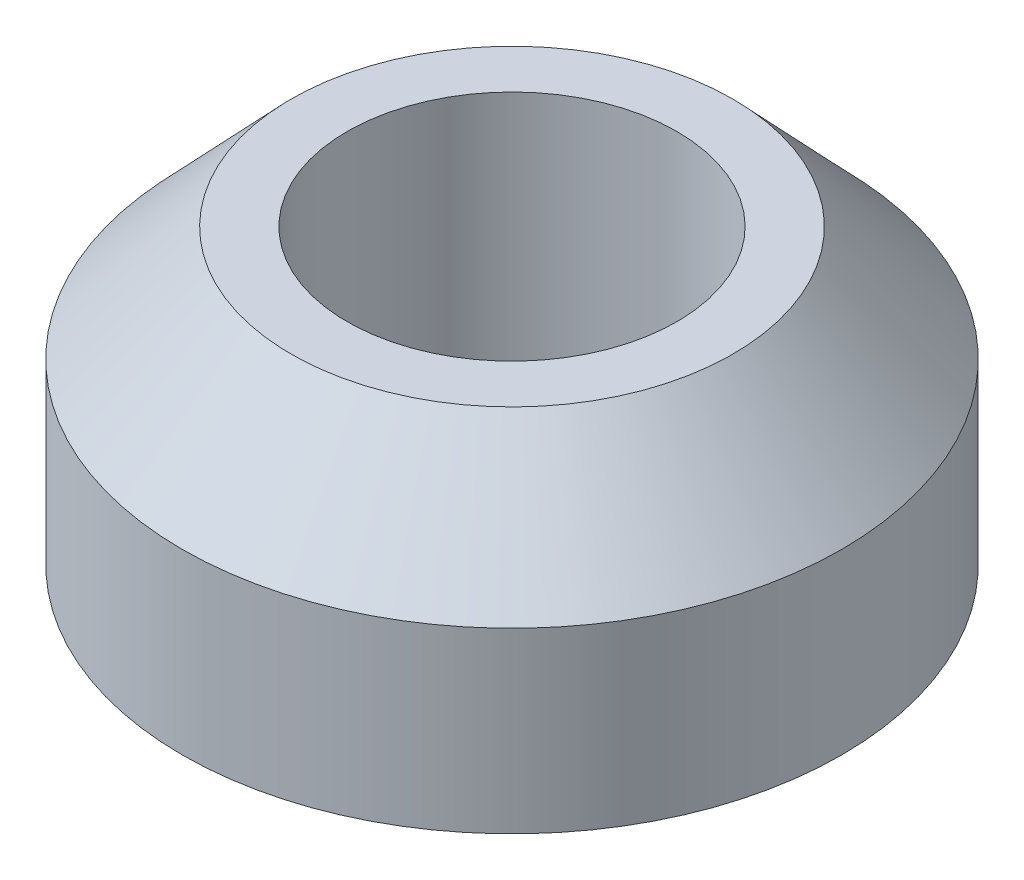
SolidWorks part; units mm, degrees
material "Alloy Steel"
ref_plane "Front Plane" through (0, 0, 0) normal (0, 0, 1) x (1, 0, 0)
ref_plane "Top Plane" through (0, 0, 0) normal (0, 1, 0) x (1, 0, 0)
ref_plane "Right Plane" through (0, 0, 0) normal (1, 0, 0) x (0, 0, -1)
sketch "Sketch2" plane through (0, 0, 0) normal (1, 0, 0) x (0, 0, -1)
  line L0 (0, 0) -> (3.175, 0) construction
  line L1 (3.175, 0) -> (3.175, 5.6388)
  line L2 (3.175, 5.6388) -> (4.2545, 5.6388)
  line L3 (4.2545, 5.6388) -> (6.35, 3.429)
  line L4 (6.35, 3.429) -> (6.35, 0)
  line L5 (6.35, 0) -> (3.175, 0)
  line L6 (0, 0) -> (0, 5.6388) construction
  dimension "D1" = 3.175
  dimension "D2" = 5.6388
  dimension "D3" = 3.175
  dimension "D4" = 3.429
  dimension "D5" = 1.0795
revolve "Revolve1" add sketch "Sketch2" angle 360 about L6
equation "\"A\"= .25'From FE13 Sus Cost List \"ebay\""
equation "\"B\"= .335"
equation "\"C\"= .5"
equation "\"D\" = .222"
equation "\"E\"= .135"
equation "\"F\"= 35"
equation "\"D1@Sketch2\"=\"A\"/2"
equation "\"D2@Sketch2\"=\"D\""
equation "\"D3@Sketch2\"=(\"C\"-\"A\")/2"
equation "\"D4@Sketch2\"=\"E\""
equation "\"D5@Sketch2\"=(\"B\"-\"A\")/2"
